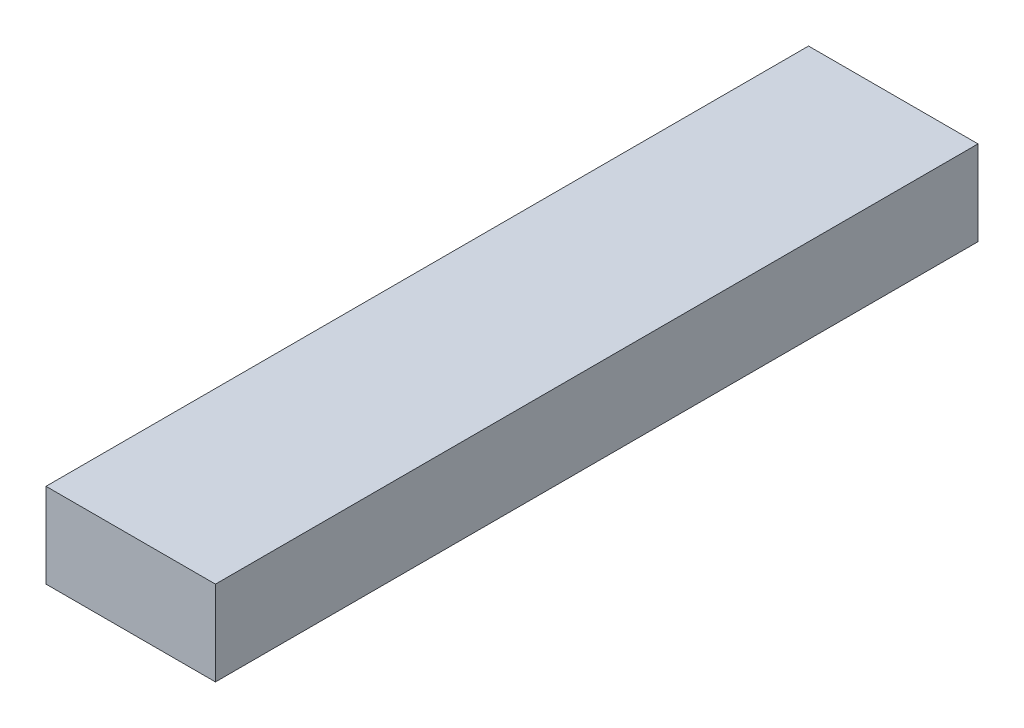
SolidWorks part; units mm, degrees
material "Custom Plastic"
ref_plane "X-Y Datum" through (0, 0, 0) normal (0, 0, 1) x (1, 0, 0)
ref_plane "X-Z Datum" through (0, 0, 0) normal (0, 1, 0) x (1, 0, 0)
ref_plane "Y-Z Datum" through (0, 0, 0) normal (1, 0, 0) x (0, 0, -1)
sketch "Sketch1" plane through (0, 0, 0) normal (0, 0, 1) x (1, 0, 0)
  line L1 (-25.4, -12.7) -> (25.4, -12.7)
  line L2 (-25.4, -12.7) -> (-25.4, 12.7)
  line L3 (-25.4, 12.7) -> (25.4, 12.7)
  line L4 (25.4, -12.7) -> (25.4, 12.7)
  line L5 (-25.4, -12.7) -> (25.4, 12.7) construction
  line L6 (-25.4, 12.7) -> (25.4, -12.7) construction
  point P0 (0, 0)
  dimension "D1" = 25.4
  dimension "D2" = 50.8
extrude "Boss-Extrude1" add sketch "Sketch1" along normal blind 228.6
